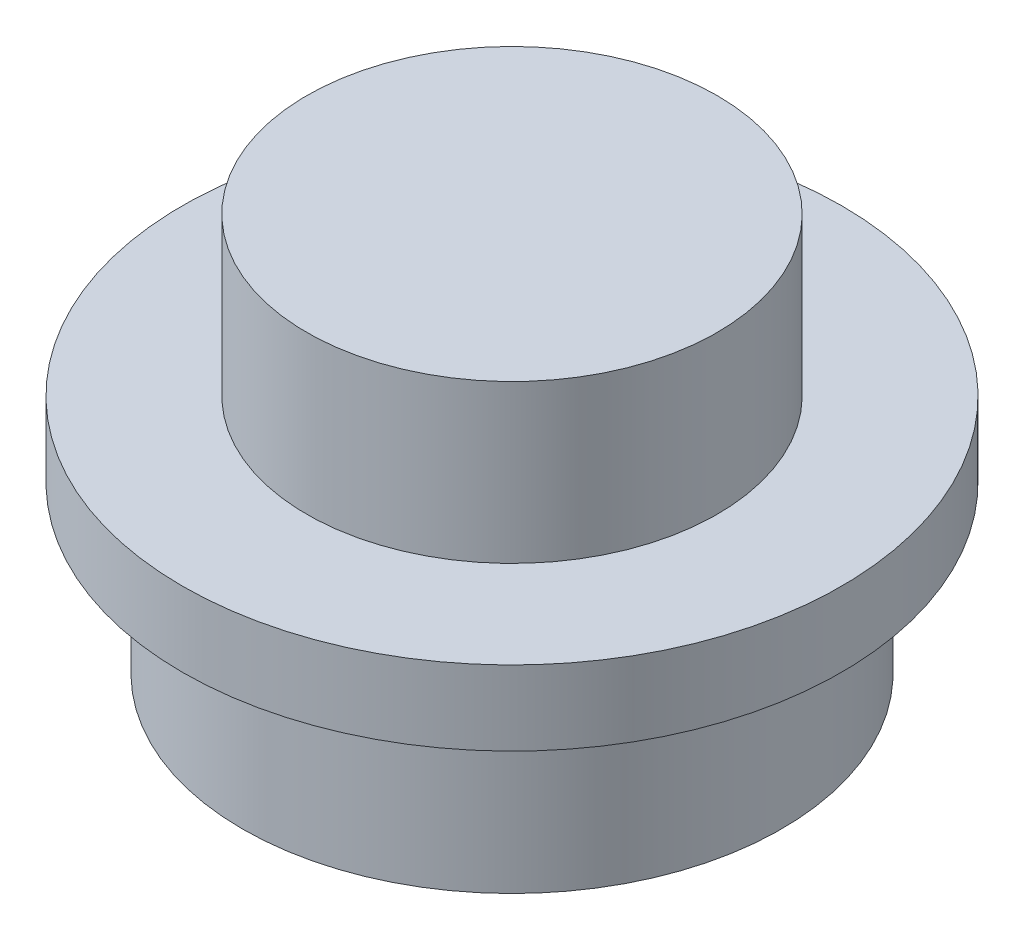
SolidWorks part; units mm, degrees
ref_plane "Front Plane" through (0, 0, 0) normal (0, 0, 1) x (1, 0, 0)
ref_plane "Top Plane" through (0, 0, 0) normal (0, 1, 0) x (1, 0, 0)
ref_plane "Right Plane" through (0, 0, 0) normal (1, 0, 0) x (0, 0, -1)
sketch "Sketch1" plane through (0, 0, 0) normal (0, 1, 0) x (1, 0, 0)
  circle A0 centre (-7.9917, -13.4054) radius 3.25
  circle A1 centre (-7.9917, -13.4054) radius 2.475
  dimension "D1" = 4.95
  dimension "D2" = 6.5
extrude "Boss-Extrude1" add sketch "Sketch1" along normal blind 2
sketch "Sketch2" plane through (0, 2, 0) normal (0, 1, 0) x (1, 0, 0)
  circle A0 centre (-7.9917, -13.4054) radius 3.975
  dimension "D1" = 7.95
extrude "Boss-Extrude2" add sketch "Sketch2" along normal blind 0.9
sketch "Sketch3" plane through (0, 2.9, 0) normal (0, 1, 0) x (-1, 0, 0)
  circle A0 centre (7.9917, 13.4054) radius 2.475
  dimension "D1" = 4.95
extrude "Boss-Extrude3" add sketch "Sketch3" along normal blind 1.9
